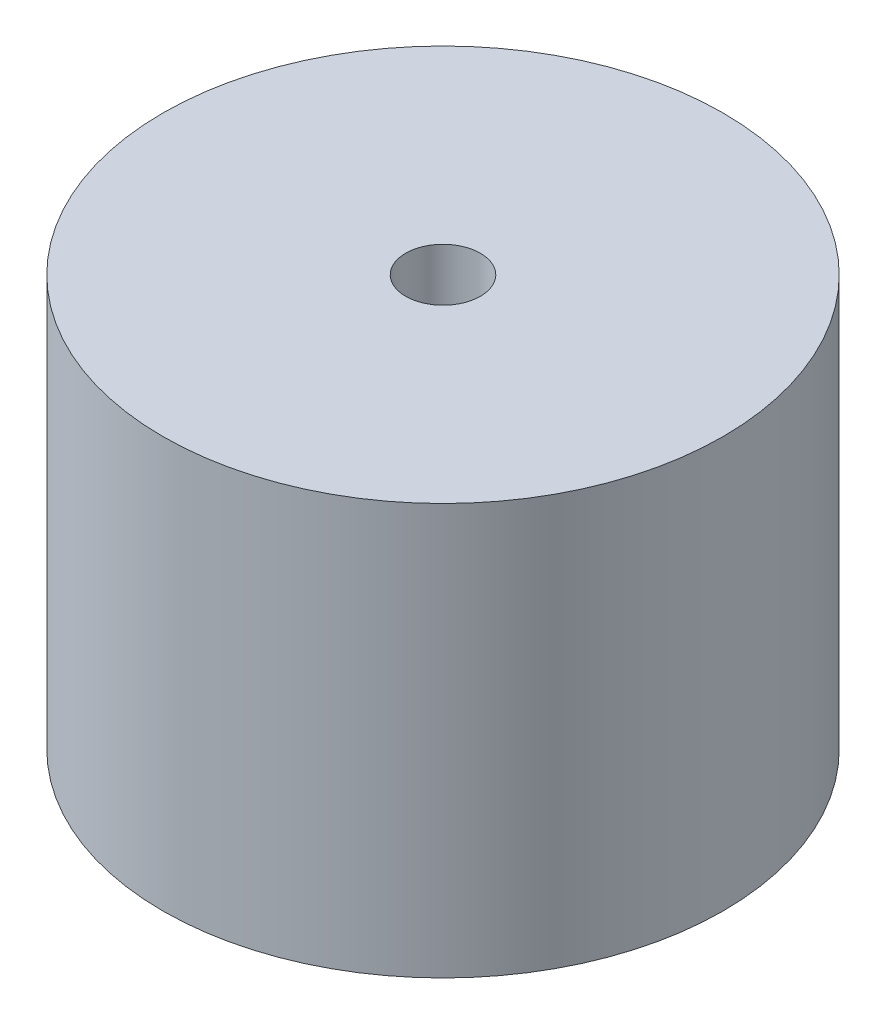
SolidWorks part; units mm, degrees
ref_plane "Front Plane" through (0, 0, 0) normal (0, 0, 1) x (1, 0, 0)
ref_plane "Top Plane" through (0, 0, 0) normal (0, 1, 0) x (1, 0, 0)
ref_plane "Right Plane" through (0, 0, 0) normal (1, 0, 0) x (0, 0, -1)
sketch "Sketch1" plane through (0, 0, 0) normal (0, 1, 0) x (1, 0, 0)
  circle A0 centre (0, 0) radius 15
  dimension "D1" = 30
extrude "Boss-Extrude1" add sketch "Sketch1" along normal blind 22
sketch "Sketch2" plane through (0, 22, 0) normal (0, 1, 0) x (1, 0, 0)
  circle A0 centre (0, 0) radius 2
  dimension "D1" = 4
extrude "Cut-Extrude1" cut sketch "Sketch2" against normal blind 5
